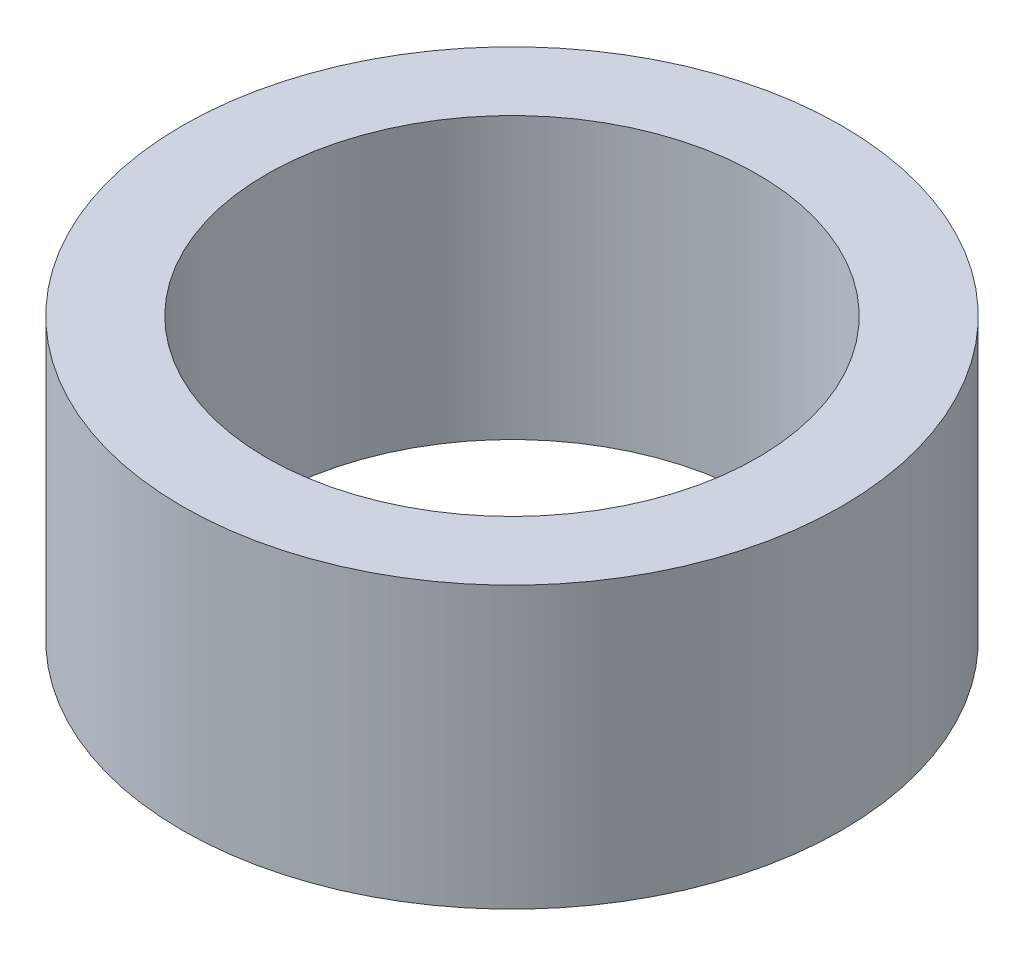
SolidWorks part; units mm, degrees
ref_plane "Front Plane" through (0, 0, 0) normal (0, 0, 1) x (1, 0, 0)
ref_plane "Top Plane" through (0, 0, 0) normal (0, 1, 0) x (1, 0, 0)
ref_plane "Right Plane" through (0, 0, 0) normal (1, 0, 0) x (0, 0, -1)
sketch "Sketch2" plane through (0, 0, 0) normal (0, 1, 0) x (1, 0, 0)
  circle A0 centre (0, 0) radius 23.5
  dimension "D1" = 47
extrude "Boss-Extrude1" add sketch "Sketch2" along normal blind 20
sketch "Sketch4" plane through (0, 20, 0) normal (0, 1, 0) x (1, 0, 0)
  circle A1 centre (0, 0) radius 17.5
  dimension "D1" = 35
extrude "Cut-Extrude1" cut sketch "Sketch4" against normal through all
